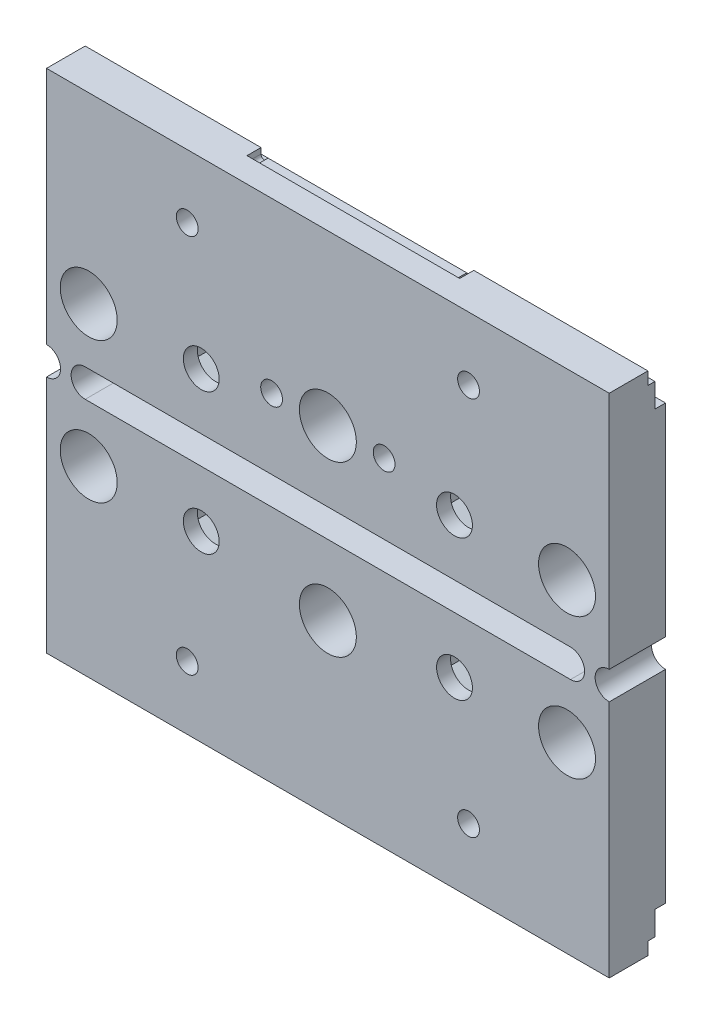
SolidWorks part; units mm, degrees
ref_plane "前视基准面" through (0, 0, 0) normal (0, 0, 1) x (1, 0, 0)
ref_plane "上视基准面" through (0, 0, 0) normal (0, 1, 0) x (1, 0, 0)
ref_plane "右视基准面" through (0, 0, 0) normal (1, 0, 0) x (0, 0, -1)
sketch "前视图草图" plane through (0, 0, 0) normal (0, 0, 1) x (1, 0, 0)
  line L0 (0, 0) -> (8.5179, 0) construction
  line L1 (0, 0) -> (0, 5.4227) construction
sketch "草图2" plane through (0, 0, 0) normal (0, 0, 1) x (1, 0, 0)
  line L0 (0, 0) -> (80, 0)
  line L1 (-200000, 0) -> (200008.5179, 0) construction
  line L2 (80, 0) -> (80, 34)
  line L3 (80, 34) -> (0, 34)
  line L4 (0, -200000) -> (0, 200005.4227) construction
  line L5 (0, 34) -> (0, 0)
  circle A0 centre (6, 8) radius 4.05
  circle A1 centre (40, 10) radius 4.05
  circle A2 centre (74, 8) radius 4.05
  dimension "D3" = 8
  dimension "D5" = 10
  dimension "D9" = 8.1
  dimension "D10" = 8.1
  dimension "D11" = 8.1
  dimension "D1" = 34
  dimension "D2" = 80
  dimension "D4" = 6
  dimension "D6" = 6
  dimension "D7" = 8
  dimension "D8" = 40
extrude "凸台-拉伸1" add sketch "草图2" along normal blind 8
sketch "草图3" plane through (0, 0, 8) normal (0, 0, 1) x (1, 0, 0)
  line L0 (16.088, 8) -> (31.4805, 8) construction
  line L1 (6, 8) -> (6, 16.8386) construction
  line L2 (74, 8) -> (74, 16.5917) construction
  line L4 (-200000, 0) -> (200008.5179, 0) construction
  circle A2 centre (22, 8) radius 2.55
  circle A3 centre (58, 8) radius 2.55
  dimension "D4" = 5.1
  dimension "D5" = 5.1
  dimension "D1" = 8
  dimension "D2" = 16
  dimension "D3" = 16
extrude "切除-拉伸1" cut sketch "草图3" against normal through all
sketch "草图4" plane through (80, 0, 0) normal (1, 0, 0) x (0, 0, -1)
  line L1 (0, -200000) -> (0, 200005.4227) construction
  line L2 (-1.5, 32.2) -> (-2.5, 32.2)
  line L3 (-2.5, 32.2) -> (-2.5, 34)
  line L4 (-8, 34) -> (0, 34) construction
  line L5 (-2.5, 34) -> (0, 34)
  line L6 (-1.5, 32.2) -> (-1.5, 28.8)
  line L7 (-1.5, 28.8) -> (0, 28.8)
  line L8 (0, 28.8) -> (0, 34)
  dimension "D1" = 3.4
  dimension "D2" = 2.5
  dimension "D3" = 1.5
  dimension "D4" = 1.8
extrude "切除-拉伸2" cut sketch "草图4" against normal through all
sketch "草图5" plane through (0, 0, 8) normal (0, 0, 1) x (1, 0, 0)
  line L0 (40, 10) -> (56.5376, 10) construction
  circle A0 centre (40, 10) radius 8 construction
  circle A1 centre (48, 10) radius 1.55
  circle A2 centre (32, 10) radius 1.55
  dimension "D1" = 3.1
  dimension "D2" = 3.1
  dimension "D3" = 16
extrude "切除-拉伸3" cut sketch "草图5" against normal through all
sketch "草图7" plane through (0, 0, 0) normal (0, 0, -1) x (-1, 0, 0)
  line L0 (-80, 0) -> (-80, 28.8) construction
  line L1 (-53.9, 5.6329) -> (-53.9, 10.3671)
  line L14 (-53.9, 10.3671) -> (-58, 12.7343)
  line L15 (-58, 12.7343) -> (-62.1, 10.3671)
  line L19 (-62.1, 10.3671) -> (-62.1, 5.6329)
  line L20 (-62.1, 5.6329) -> (-58, 3.2657)
  line L21 (-58, 3.2657) -> (-53.9, 5.6329)
  line L22 (-26.1, 5.6329) -> (-22, 3.2657)
  line L23 (-22, 3.2657) -> (-17.9, 5.6329)
  line L24 (-17.9, 5.6329) -> (-17.9, 10.3671)
  line L25 (-17.9, 10.3671) -> (-22, 12.7343)
  line L26 (-22, 12.7343) -> (-26.1, 10.3671)
  line L27 (-26.1, 10.3671) -> (-26.1, 5.6329)
  circle A6 centre (-58, 8) radius 4.1 construction
  circle A10 centre (-22, 8) radius 4.1 construction
  dimension "D1" = 8.2
extrude "切除-拉伸4" cut sketch "草图7" against normal blind 6
sketch "草图8" plane through (0, 0, 0) normal (0, 0, -1) x (-1, 0, 0)
  line L0 (-80, 0) -> (-80, 28.8) construction
  line L1 (-48, 6.7091) -> (-45.15, 8.3546)
  line L5 (-45.15, 8.3546) -> (-45.15, 11.6454)
  line L6 (-45.15, 11.6454) -> (-48, 13.2909)
  line L7 (-48, 13.2909) -> (-50.85, 11.6454)
  line L8 (-50.85, 11.6454) -> (-50.85, 8.3546)
  line L9 (-50.85, 8.3546) -> (-48, 6.7091)
  line L10 (-32, 6.7091) -> (-29.15, 8.3546)
  line L11 (-29.15, 8.3546) -> (-29.15, 11.6454)
  line L12 (-29.15, 11.6454) -> (-32, 13.2909)
  line L13 (-32, 13.2909) -> (-34.85, 11.6454)
  line L14 (-34.85, 11.6454) -> (-34.85, 8.3546)
  line L15 (-34.85, 8.3546) -> (-32, 6.7091)
  circle A2 centre (-48, 10) radius 2.85 construction
  circle A3 centre (-32, 10) radius 2.85 construction
  dimension "D1" = 5.7
extrude "切除-拉伸5" cut sketch "草图8" against normal blind 4.5
sketch "草图20" plane through (0, 0, 0) normal (0, 0, -1) x (-1, 0, 0)
  circle A0 centre (-40, 10) radius 5.5
  dimension "D1" = 11
sketch "草图25" plane through (0, 0, 0) normal (0, 0, -1) x (-1, 0, 0)
  line L0 (-51.4471, 25) -> (-40.1512, 25) construction
  line L1 (-60, 37.1428) -> (-60, 21.9179) construction
  line L2 (-20, 37.1428) -> (-20, 21.9179) construction
  line L3 (0, 34) -> (-80, 34) construction
  line L4 (-80, 0) -> (-80, 28.8) construction
  line L5 (0, -200000) -> (0, 200005.4227) construction
  circle A0 centre (-60, 25) radius 1.55
  circle A1 centre (-20, 25) radius 1.55
  dimension "D4" = 3.1
  dimension "D5" = 3.1
  dimension "D1" = 9
  dimension "D2" = 20
  dimension "D3" = 20
extrude "切除-拉伸13" cut sketch "草图25" against normal through all
sketch "草图19" plane through (0, 0, 2.5) normal (0, 0, -1) x (-1, 0, 0)
  line L0 (0, 34) -> (-80, 34) construction
  line L1 (-25, 34) -> (-55.2479, 34)
  line L2 (-25, 34) -> (-25, 33.2)
  line L3 (-26, 33.2) -> (-54.2479, 33.2)
  line L4 (-55.2479, 34) -> (-55.2479, 33.2)
  line L5 (0, -200000) -> (0, 200005.4227) construction
  line L7 (0, 32.2) -> (-80, 32.2) construction
  line L8 (-56.3335, 32.7) -> (-52.9089, 32.7) construction
  line L9 (-55.2479, 1028.5823) -> (-55.2479, 33.2) construction
  line L10 (-25, 1028.5823) -> (-25, 32.7) construction
  line L11 (-55.2479, 32.7) -> (-55.2479, -973.3) construction
  line L12 (-25, 32.7) -> (-25, -973.3) construction
  arc A3 (-55.2479, 33.2) -> (-54.2479, 33.2) centre (-54.7479, 33.2) ccw
  arc A6 (-26, 33.2) -> (-25, 33.2) centre (-25.5, 33.2) ccw
  dimension "D3" = 1
  dimension "D4" = 1
  dimension "D2" = 0.8
  dimension "D1" = 0.5
  dimension "D9" = 25
extrude "切除-拉伸11" cut sketch "草图19" against normal blind 2
sketch "草图22" plane through (0, 0, 8) normal (0, 0, 1) x (1, 0, 0)
  line L1 (0, -200000) -> (0, 200005.4227) construction
  line L2 (0, -4) -> (5.5, -4)
  line L4 (80, 0) -> (74.5, 0)
  line L5 (3.5, 1.9875) -> (3.5, -4.1402) construction
  line L6 (76.5, -11.5647) -> (76.5, -5.1636) construction
  line L7 (80, 0) -> (80, 34) construction
  line L8 (74.5, -4) -> (80, -4)
  line L9 (5.5, 0) -> (0, 0)
  line L10 (78, -2.9635) -> (78, -4.3032) construction
  line L11 (2, -8.393) -> (2, -15.1693) construction
  arc A0 (5.5, 0) -> (5.5, -4) centre (5.5, -2) ccw
  arc A1 (74.5, -4) -> (74.5, 0) centre (74.5, -2) ccw
  arc A2 (0, -4) -> (0, 0) centre (0, -2) ccw
  arc A3 (80, 0) -> (80, -4) centre (80, -2) ccw
  dimension "D1" = 3.5
  dimension "D2" = 3.5
  dimension "D3" = 4
  dimension "D4" = 2
  dimension "D5" = 2
extrude "凸台-拉伸2" add sketch "草图22" against normal blind 8
ref_plane "基准面1" through (0, -2, 0) normal (0, -1, 0) x (-1, 0, 0)
mirror "镜向2" about plane through (0, -2, 0) normal (0, -1, 0) of "切除-拉伸1", "凸台-拉伸1", "切除-拉伸2", "切除-拉伸11", "切除-拉伸13", "切除-拉伸4"
sketch "草图23" plane through (0, 0, 0) normal (0, 0, -1) x (-1, 0, 0)
  line L0 (-80, 0) -> (0, 0)
  line L1 (0, 0) -> (0, -4)
  line L2 (0, -4) -> (-80, -4)
  line L3 (-80, -4) -> (-80, 0)
sketch "草图26" plane through (0, 0, 0) normal (0, 0, -1) x (-1, 0, 0)
  circle A0 centre (-40, -14) radius 5.5
  dimension "D1" = 11
extrude "切除-拉伸14" [suppressed] cut sketch "草图26" against normal blind 7
sketch "草图24" plane through (0, 0, 8) normal (0, 0, 1) x (1, 0, 0)
  line L0 (80, -4) -> (80, 0)
  line L1 (80, 0) -> (0, 0)
  line L2 (0, 0) -> (0, -4)
  line L3 (0, -4) -> (80, -4)
